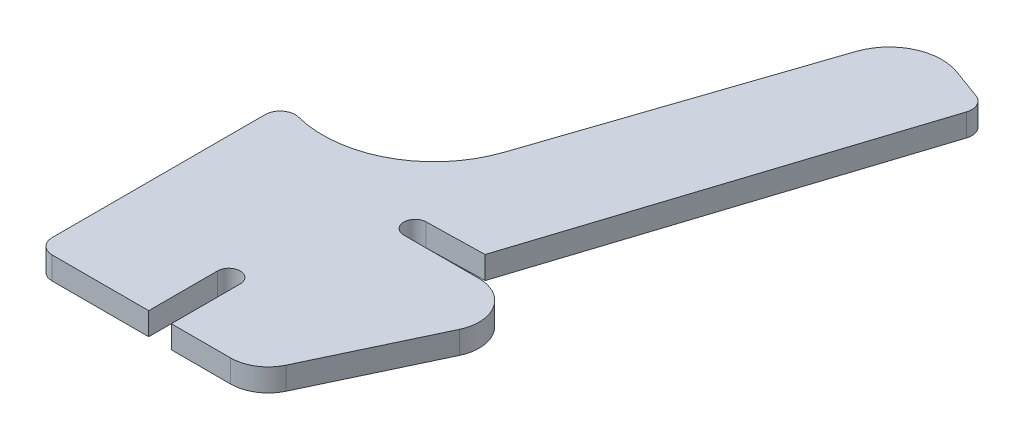
SolidWorks part; units mm, degrees
ref_plane "Front Plane" through (0, 0, 0) normal (0, 0, 1) x (1, 0, 0)
ref_plane "Top Plane" through (0, 0, 0) normal (0, 1, 0) x (1, 0, 0)
ref_plane "Right Plane" through (0, 0, 0) normal (1, 0, 0) x (0, 0, -1)
sketch "Sketch1" plane through (0, 0, 0) normal (0, 1, 0) x (1, 0, 0)
  line L0 (0, 33.06) -> (0, 0)
  line L1 (0, 0) -> (14.8, 0)
  line L2 (14.8, 0) -> (14.8, 9.13)
  line L3 (17.8, 9.13) -> (17.8, 0)
  line L4 (17.8, 0) -> (28.82, 0)
  line L5 (28.82, 0) -> (40.93, 25.6)
  line L6 (40.93, 25.6) -> (23.0399, 25.6)
  line L7 (23.008, 28.5997) -> (30.66, 28.7624)
  line L8 (30.66, 28.7624) -> (46.79, 78.9)
  line L9 (46.79, 78.9) -> (34.22, 83.4847)
  line L10 (34.22, 83.4847) -> (20.1714, 41.7583)
  arc A0 (14.8, 9.13) -> (17.8, 9.13) centre (16.3, 9.13) cw
  arc A1 (23.0399, 25.6) -> (23.008, 28.5997) centre (23.0399, 27.1) cw
  arc A2 (20.1714, 41.7583) -> (0, 33.06) centre (6.1787, 46.4694) cw
  point P0 (18.6466, 41.9962)
  point P18 (21.54, 27.0841)
  point P21 (16.3, 10.63)
  point P28 (40.505, 81.1924)
  dimension "D3" = 1.5
  dimension "D9" = 9.12
  dimension "D15" = 14.7645
  dimension "D1" = 14.8
  dimension "D2" = 10.63
  dimension "D4" = 40.93
  dimension "D5" = 25.6
  dimension "11.02" = 11.02
  dimension "D6" = 30.66
  dimension "D7" = 52.43
  dimension "D8" = 33.06
  dimension "D10" = 13.38
  dimension "D11" = 46.79
  dimension "D12" = 78.9
  dimension "D13" = 34.22
  dimension "D14" = 13.4094
extrude "Boss-Extrude1" add sketch "Sketch1" along normal blind 3
fillet "Fillet1" radius 5 1 edges at (40.93, 1.5, -25.6)
fillet "Fillet2" radius 2 1 edges at (0, 1.5, -33.06)
fillet "Fillet3" radius 7 1 edges at (34.22, 1.5, -83.4847)
fillet "Fillet4" radius 2 2 edges at (0, 1.5, 0) (46.79, 1.5, -78.9)
fillet "Fillet5" radius 5 1 edges at (28.82, 1.5, 0)
